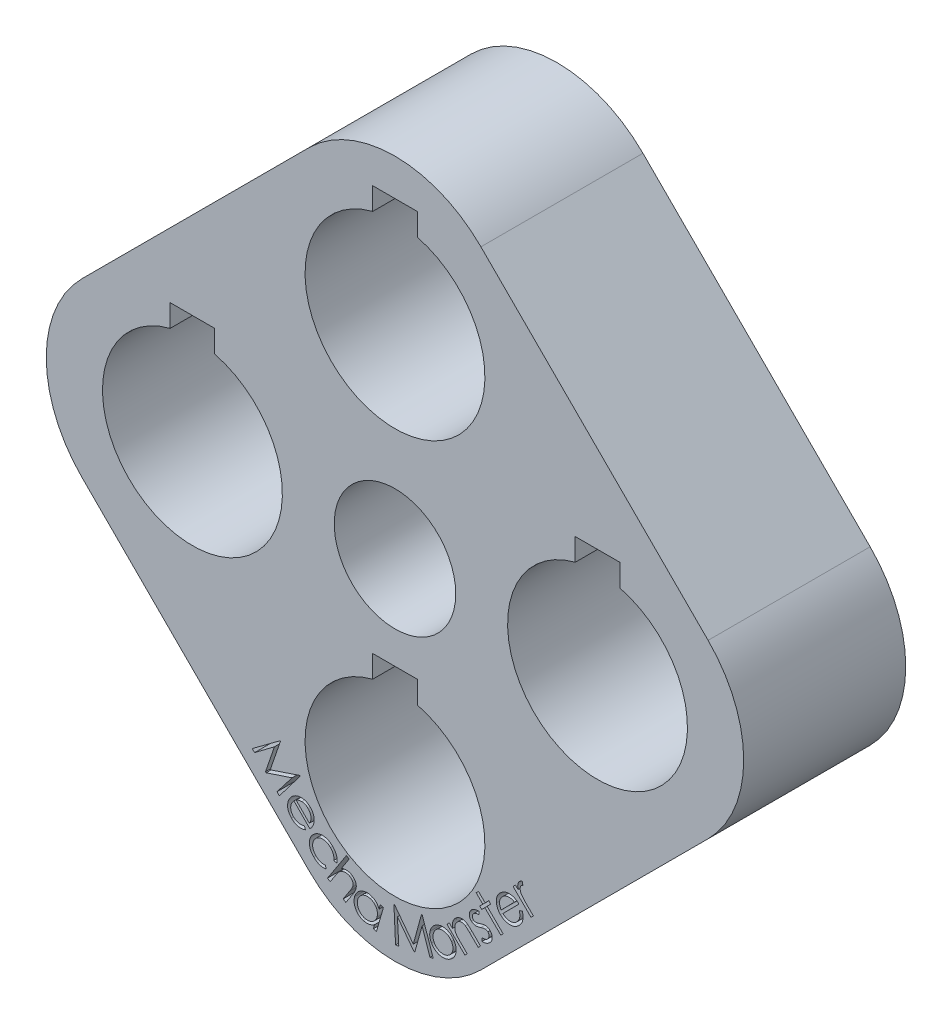
SolidWorks part; units mm, degrees
ref_plane "Front Plane" through (0, 0, 0) normal (0, 0, 1) x (1, 0, 0)
ref_plane "Top Plane" through (0, 0, 0) normal (0, 1, 0) x (1, 0, 0)
ref_plane "Right Plane" through (0, 0, 0) normal (1, 0, 0) x (0, 0, -1)
sketch "Sketch1" plane through (0, 0, 0) normal (0, 0, 1) x (1, 0, 0)
  line L0 (-2.75, 13.504) -> (2.75, 13.504)
  line L1 (0, -24.2553) -> (49.2553, 25)
  line L2 (0, 74.2553) -> (49.2553, 25)
  line L3 (-2.75, 63.504) -> (2.75, 63.504)
  line L4 (-2.75, 13.504) -> (-2.75, 10.754)
  line L5 (2.75, 13.504) -> (2.75, 10.754)
  line L6 (0, 74.2553) -> (-49.2553, 25)
  line L9 (-2.75, 63.504) -> (-2.75, 60.754)
  line L10 (2.75, 63.504) -> (2.75, 60.754)
  line L11 (0, -24.2553) -> (-49.2553, 25)
  line L12 (0, 0) -> (0, 50) construction
  line L13 (0, 25) -> (25, 25) construction
  line L14 (0, 25) -> (-25, 25) construction
  line L15 (22.25, 38.504) -> (27.75, 38.504)
  line L18 (22.25, 38.504) -> (22.25, 35.754)
  line L19 (27.75, 38.504) -> (27.75, 35.754)
  line L21 (-27.75, 38.504) -> (-22.25, 38.504)
  line L24 (-27.75, 38.504) -> (-27.75, 35.754)
  line L25 (-22.25, 38.504) -> (-22.25, 35.754)
  arc A0 (-2.75, 10.754) -> (2.75, 10.754) centre (0, 0) ccw
  circle A1 centre (0, 25) radius 7.5
  arc A2 (-2.75, 60.754) -> (2.75, 60.754) centre (0, 50) ccw
  arc A4 (22.25, 35.754) -> (27.75, 35.754) centre (25, 25) ccw
  arc A6 (-27.75, 35.754) -> (-22.25, 35.754) centre (-25, 25) ccw
extrude "Boss-Extrude1" add sketch "Sketch1" along normal blind 20
fillet "Fillet1" radius 15 4 edges at (0, 74.2553, 10) (-49.2553, 25, 10) (0, -24.2553, 10) (49.2553, 25, 10)
sketch "Sketch4" plane through (0, 0, 20) normal (0, 0, 1) x (1, 0, 0)
  text T0 "Mecha Monster" font "Century Gothic" height in points 16
extrude "Cut-Extrude4" cut sketch "Sketch4" against normal blind 3
